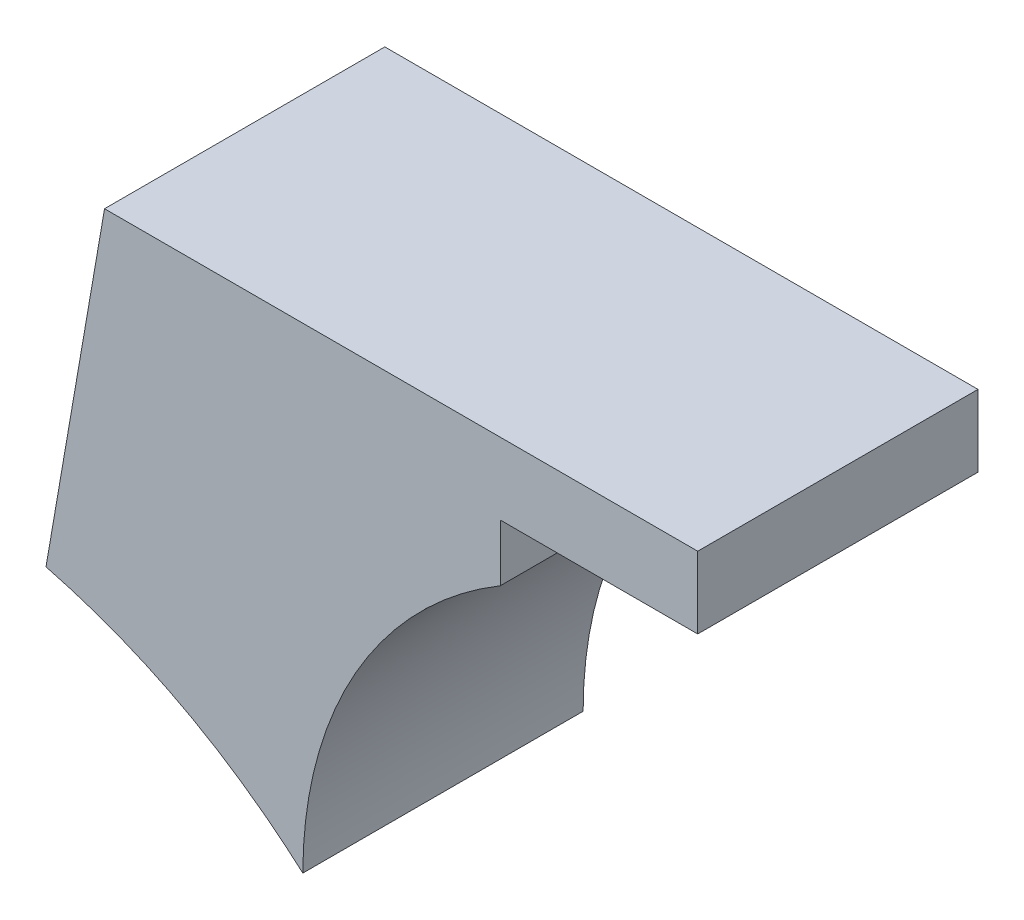
SolidWorks part; units mm, degrees
ref_plane "Front Plane" through (0, 0, 0) normal (0, 0, 1) x (1, 0, 0)
ref_plane "Top Plane" through (0, 0, 0) normal (0, 1, 0) x (1, 0, 0)
ref_plane "Right Plane" through (0, 0, 0) normal (1, 0, 0) x (0, 0, -1)
sketch "Sketch1" plane through (0, 0, 0) normal (0, 0, 1) x (1, 0, 0)
  line L0 (149.8559, -58.0677) -> (149.8559, 43.8748)
  line L1 (149.8559, 43.8748) -> (107.405, 43.8748)
  line L2 (107.405, 43.8748) -> (94.8747, -28.7787)
  line L3 (149.8559, 43.8748) -> (234.3838, 43.8748)
  line L4 (234.3838, 43.8748) -> (234.3838, 28.5235)
  line L5 (234.3838, 28.5235) -> (149.8559, 28.5235)
  line L6 (22.9369, 43.8748) -> (42.8134, 43.8748)
  line L7 (101.1845, -30.5679) -> (97.3203, -43.0485)
  line L8 (97.3203, -43.0485) -> (130.0729, -58.0677)
  line L9 (130.0729, -58.0677) -> (149.8559, -58.0677)
  line L10 (174.4912, 2.4364) -> (184.5094, -7.343)
  line L11 (119.7474, 43.8748) -> (192.854, 43.8748)
  line L12 (119.7474, 43.8748) -> (119.7474, 57.8748)
  line L13 (119.7474, 57.8748) -> (192.854, 57.8748)
  line L14 (192.854, 43.8748) -> (192.854, 57.8748)
  line L15 (192.1198, 28.5235) -> (192.1198, 0.9943)
  arc A0 (149.8559, -58.0677) -> (234.3838, 28.5235) centre (236.4723, -58.0677) cw
  circle A1 centre (109.0791, -40.7397) radius 2.5625
  circle A2 centre (128.1677, -49.4932) radius 2.5625
  circle A3 centre (136.4752, 50.8748) radius 2.5625
  circle A4 centre (185.5073, 3.7004) radius 2.563
  circle A5 centre (156.4752, 50.8748) radius 2.5625
  circle A6 centre (176.4752, 50.8748) radius 2.5625
  spline S0 degree 2 poles (94.8747, -28.7787) (125.8193, -36.7659) (149.8559, -58.0677) knots 0 0 0 1 1 1
  spline S1 degree 3 poles (45.9646, 43.8753) (45.1115, 43.8752) (43.0471, 43.875) (39.7711, 43.8742) (36.1357, 43.8733) (32.0958, 43.8731) (27.6523, 43.8739) (23.1651, 43.8749) (20.2937, 43.8752) (19.0374, 43.8753) knots 0 0 0 0 0.09512 0.23016 0.365129 0.500054 0.679977 0.859975 1 1 1 1 construction
  spline S2 degree 2 poles (184.5094, -7.343) (204.9306, 17.0782) (234.3838, 28.5235) knots 0 0 0 1 1 1
  dimension "D3" = 5.125
  dimension "D4" = 5.125
  dimension "D9" = 5.125
  dimension "D11" = 5.126
  dimension "D1" = 15.3513
  dimension "D2" = 15.3513
  dimension "D5" = 21
  dimension "D6" = 7
  dimension "D7" = 7
  dimension "D8" = 14
  dimension "D10" = 7
  dimension "D12" = 14
  dimension "D13" = 3
sketch "Sketch2" plane through (0, 0, 0) normal (0, 0, 1) x (1, 0, 0)
  line L0 (149.8559, -58.0677) -> (149.8559, 43.8748)
  line L1 (149.8559, 43.8748) -> (107.405, 43.8748)
  line L2 (107.405, 43.8748) -> (94.8747, -28.7787)
  line L3 (149.8559, 43.8748) -> (234.3838, 43.8748)
  line L4 (234.3838, 43.8748) -> (234.3838, 28.5235)
  line L5 (234.3838, 28.5235) -> (149.8559, 28.5235)
  line L6 (22.9369, 43.8748) -> (42.8134, 43.8748)
  line L7 (101.1845, -30.5679) -> (97.3203, -43.0485)
  line L8 (97.3203, -43.0485) -> (130.0729, -58.0677)
  line L9 (130.0729, -58.0677) -> (149.8559, -58.0677)
  line L10 (174.4912, 2.4364) -> (184.5094, -7.343)
  line L11 (119.7474, 43.8748) -> (192.854, 43.8748)
  line L12 (119.7474, 43.8748) -> (119.7474, 57.8748)
  line L13 (119.7474, 57.8748) -> (192.854, 57.8748)
  line L14 (192.854, 43.8748) -> (192.854, 57.8748)
  line L15 (192.1198, 28.5235) -> (192.1198, 0.9943)
  arc A0 (149.8559, -58.0677) -> (234.3838, 28.5235) centre (236.4723, -58.0677) cw
  circle A1 centre (109.0791, -40.7397) radius 2.5625
  circle A2 centre (128.1677, -49.4932) radius 2.5625
  circle A3 centre (136.4752, 50.8748) radius 2.5625
  circle A4 centre (185.5073, 3.7004) radius 2.563
  circle A5 centre (156.4752, 50.8748) radius 2.5625
  circle A6 centre (176.4752, 50.8748) radius 2.5625
  spline S0 degree 2 poles (94.8747, -28.7787) (125.8193, -36.7659) (149.8559, -58.0677) knots 0 0 0 1 1 1
  spline S2 degree 2 poles (184.5094, -7.343) (204.9306, 17.0782) (234.3838, 28.5235) knots 0 0 0 1 1 1
  dimension "D3" = 5.125
  dimension "D4" = 5.125
  dimension "D9" = 5.125
  dimension "D11" = 5.126
  dimension "D1" = 15.3513
  dimension "D2" = 15.3513
  dimension "D5" = 21
  dimension "D6" = 7
  dimension "D7" = 7
  dimension "D8" = 14
  dimension "D10" = 7
  dimension "D12" = 14
  dimension "D13" = 3
sketch "Sketch3" plane through (0, 0, 0) normal (0, 0, 1) x (1, 0, 0)
  line L0 (149.8559, -58.0677) -> (149.8559, 43.8748)
  line L1 (149.8559, 43.8748) -> (107.405, 43.8748)
  line L2 (107.405, 43.8748) -> (94.8747, -28.7787)
  line L3 (149.8559, 43.8748) -> (234.3838, 43.8748)
  line L4 (234.3838, 43.8748) -> (234.3838, 28.5235)
  line L5 (234.3838, 28.5235) -> (149.8559, 28.5235)
  line L6 (22.9369, 43.8748) -> (42.8134, 43.8748)
  line L7 (101.1845, -30.5679) -> (97.3203, -43.0485)
  line L8 (97.3203, -43.0485) -> (130.0729, -58.0677)
  line L9 (130.0729, -58.0677) -> (149.8559, -58.0677)
  line L10 (174.4912, 2.4364) -> (184.5094, -7.343)
  line L11 (119.7474, 43.8748) -> (192.854, 43.8748)
  line L12 (119.7474, 43.8748) -> (119.7474, 57.8748)
  line L13 (119.7474, 57.8748) -> (192.854, 57.8748)
  line L14 (192.854, 43.8748) -> (192.854, 57.8748)
  line L15 (192.1198, 28.5235) -> (192.1198, 0.9943)
  arc A0 (149.8559, -58.0677) -> (234.3838, 28.5235) centre (236.4723, -58.0677) cw
  circle A1 centre (109.0791, -40.7397) radius 2.5625
  circle A2 centre (128.1677, -49.4932) radius 2.5625
  circle A3 centre (136.4752, 50.8748) radius 2.5625
  circle A4 centre (185.5073, 3.7004) radius 2.563
  circle A5 centre (156.4752, 50.8748) radius 2.5625
  circle A6 centre (176.4752, 50.8748) radius 2.5625
  spline S0 degree 2 poles (94.8747, -28.7787) (125.8193, -36.7659) (149.8559, -58.0677) knots 0 0 0 1 1 1
  spline S2 degree 2 poles (184.5094, -7.343) (204.9306, 17.0782) (234.3838, 28.5235) knots 0 0 0 1 1 1
  dimension "D3" = 5.125
  dimension "D4" = 5.125
  dimension "D9" = 5.125
  dimension "D11" = 5.126
  dimension "D1" = 15.3513
  dimension "D2" = 15.3513
  dimension "D5" = 21
  dimension "D6" = 7
  dimension "D7" = 7
  dimension "D8" = 14
  dimension "D10" = 7
  dimension "D12" = 14
  dimension "D13" = 3
sketch "Sketch4" plane through (0, 0, 0) normal (0, 0, 1) x (1, 0, 0)
  line L0 (149.8559, -58.0677) -> (149.8559, 43.8748)
  line L1 (149.8559, 43.8748) -> (107.405, 43.8748)
  line L2 (107.405, 43.8748) -> (94.8747, -28.7787)
  line L3 (149.8559, 43.8748) -> (234.3838, 43.8748)
  line L4 (234.3838, 43.8748) -> (234.3838, 28.5235)
  line L5 (234.3838, 28.5235) -> (149.8559, 28.5235)
  line L6 (22.9369, 43.8748) -> (42.8134, 43.8748)
  line L7 (101.1845, -30.5679) -> (97.3203, -43.0485)
  line L8 (97.3203, -43.0485) -> (130.0729, -58.0677)
  line L9 (130.0729, -58.0677) -> (149.8559, -58.0677)
  line L10 (174.4912, 2.4364) -> (184.5094, -7.343)
  line L11 (119.7474, 43.8748) -> (192.854, 43.8748)
  line L12 (119.7474, 43.8748) -> (119.7474, 57.8748)
  line L13 (119.7474, 57.8748) -> (192.854, 57.8748)
  line L14 (192.854, 43.8748) -> (192.854, 57.8748)
  line L15 (192.1198, 28.5235) -> (192.1198, 0.9943)
  arc A0 (149.8559, -58.0677) -> (234.3838, 28.5235) centre (236.4723, -58.0677) cw
  circle A1 centre (109.0791, -40.7397) radius 2.5625
  circle A2 centre (128.1677, -49.4932) radius 2.5625
  circle A3 centre (136.4752, 50.8748) radius 2.5625
  circle A4 centre (185.5073, 3.7004) radius 2.563
  circle A5 centre (156.4752, 50.8748) radius 2.5625
  circle A6 centre (176.4752, 50.8748) radius 2.5625
  spline S0 degree 2 poles (94.8747, -28.7787) (125.8193, -36.7659) (149.8559, -58.0677) knots 0 0 0 1 1 1
  spline S2 degree 2 poles (184.5094, -7.343) (204.9306, 17.0782) (234.3838, 28.5235) knots 0 0 0 1 1 1
  dimension "D3" = 5.125
  dimension "D4" = 5.125
  dimension "D9" = 5.125
  dimension "D11" = 5.126
  dimension "D1" = 15.3513
  dimension "D2" = 15.3513
  dimension "D5" = 21
  dimension "D6" = 7
  dimension "D7" = 7
  dimension "D8" = 14
  dimension "D10" = 7
  dimension "D12" = 14
  dimension "D13" = 3
extrude "rightM" add sketch "Sketch1" along normal blind 30 contours L5 L4 L3 L0 | L0 A0 L15 L5 | L2 S0 L0 L1
extrude "leftM" add sketch "Sketch2" against normal blind 30 contours L5 L4 L3 L0 | L2 S0 L0 L1 | L0 A0 L15 L5
